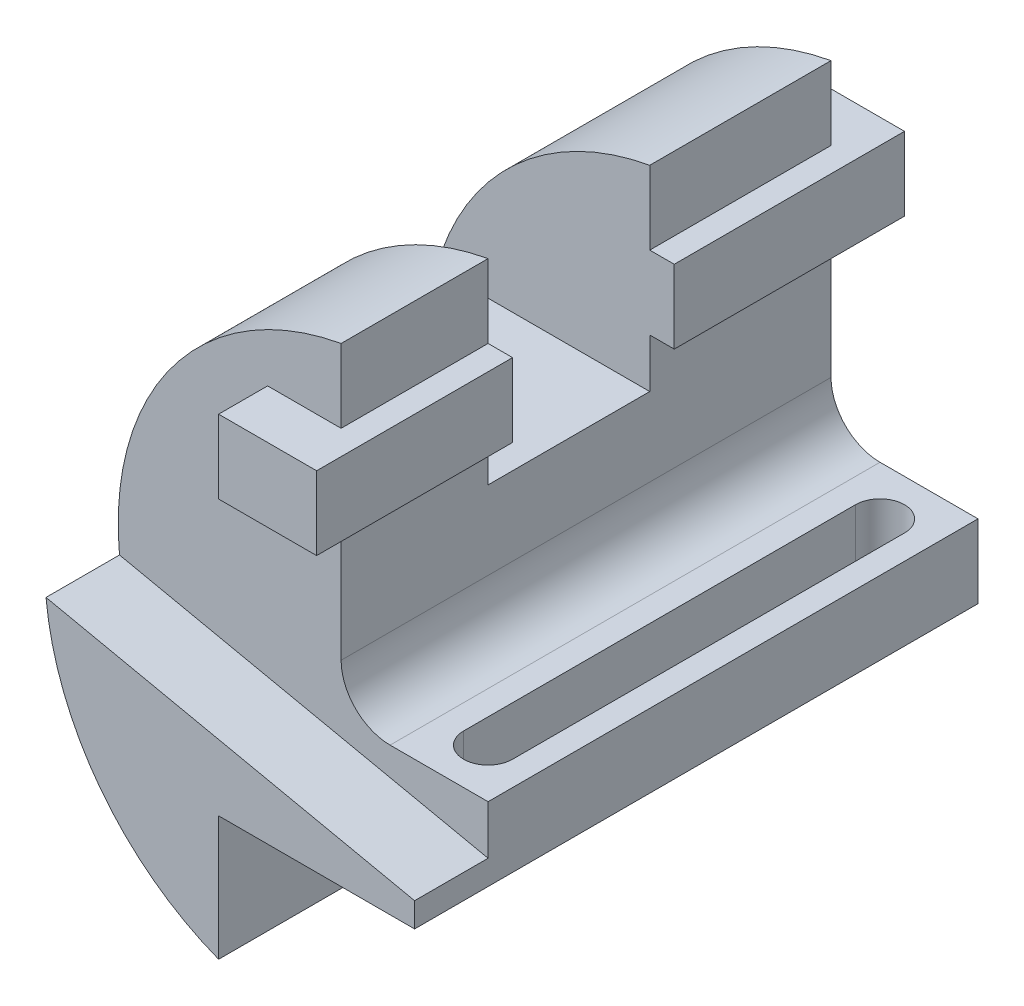
SolidWorks part; units mm, degrees
material "1060 Alloy"
ref_plane "Front Plane" through (0, 0, 0) normal (0, 0, 1) x (1, 0, 0)
ref_plane "Top Plane" through (0, 0, 0) normal (0, 1, 0) x (1, 0, 0)
ref_plane "Right Plane" through (0, 0, 0) normal (1, 0, 0) x (0, 0, -1)
sketch "Sketch1" plane through (0, 0, 0) normal (0, 0, 1) x (1, 0, 0)
  line L0 (0, 0) -> (-40, 0)
  line L1 (-40, 0) -> (-40, -25.3628)
  line L2 (0, 0) -> (0, 15)
  line L3 (0, 15) -> (-30, 15)
  line L4 (-30, 15) -> (-30, 81)
  arc A0 (-40, -25.3628) -> (-30, 81) centre (-20, 26.4083) cw
  dimension "D5" = 55.5
  dimension "D1" = 40
  dimension "D2" = 15
  dimension "D3" = 30
  dimension "D4" = 10
  dimension "D6" = 66
extrude "Boss-Extrude1" add sketch "Sketch1" along normal blind 115
sketch "Sketch2" plane through (0, 0, 115) normal (0, 0, 1) x (1, 0, 0)
  line L0 (0, 5) -> (-75.235, 20.9917)
  line L1 (0, 0) -> (0, 15) construction
  line L7 (0, 0) -> (0, 15)
  line L8 (0, 15) -> (-30, 15)
  line L9 (-30, 15) -> (-30, 81)
  line L10 (-40, -25.3628) -> (-40, 0)
  line L11 (-40, 0) -> (0, 0)
  line L12 (0, 5) -> (0, 15)
  line L13 (0, 15) -> (-30, 15)
  line L14 (-30, 15) -> (-30, 81)
  arc A1 (-30, 81) -> (-40, -25.3628) centre (-20, 26.4083) ccw
  arc A2 (-30, 81) -> (-75.235, 20.9917) centre (-20, 26.4083) ccw
  dimension "D1" = 78
  dimension "D2" = 5
  dimension "D3" = 0
extrude "Cut-Extrude1" cut sketch "Sketch2" against normal blind 15
sketch "Sketch3" plane through (0, 0, 0) normal (0, 0, -1) x (-1, 0, 0)
  line L0 (30, 15) -> (30, 81) construction
  line L1 (25, 66) -> (45, 66)
  line L2 (25, 66) -> (25, 51)
  line L3 (25, 51) -> (45, 51)
  line L4 (45, 66) -> (45, 51)
  dimension "D1" = 5
  dimension "D2" = 20
  dimension "D3" = 15
  dimension "D4" = 15
extrude "Boss-Extrude2" add sketch "Sketch3" against normal offset from surface 5 and the other way blind 10 up to face at (-32.3604, -0.8725, 115)
sketch "Sketch4" plane through (-30, 0, 0) normal (1, 0, 0) x (0, 0, -1)
  line L0 (-100, 81) -> (0, 81) construction
  line L1 (-70, 81) -> (-37, 81)
  line L2 (-70, 81) -> (-70, 41)
  line L3 (-70, 41) -> (-37, 41)
  line L4 (-37, 81) -> (-37, 41)
  line L5 (-100, 66) -> (-100, 81) construction
  line L6 (10, 51) -> (-110, 51) construction
  dimension "D1" = 33
  dimension "D2" = 30
  dimension "D3" = 10
extrude "Cut-Extrude3" cut sketch "Sketch4" against normal through all both and the other way through all
sketch "Sketch5" plane through (0, 15, 0) normal (0, 1, 0) x (1, 0, 0)
  line L0 (-10, -10) -> (-10, -90) construction
  line L1 (-5, -10) -> (-5, -90)
  line L2 (-15, -10) -> (-15, -90)
  line L3 (0, -100) -> (0, 0) construction
  line L4 (-75.235, -100) -> (0, -100) construction
  arc A0 (-5, -10) -> (-15, -10) centre (-10, -10) ccw
  arc A1 (-15, -90) -> (-5, -90) centre (-10, -90) ccw
  point P2 (-10, -50)
  dimension "D1" = 80
  dimension "D2" = 10
  dimension "D3" = 10
  dimension "D4" = 10
extrude "Cut-Extrude4" cut sketch "Sketch5" against normal through all both and the other way through all
fillet "Fillet1" radius 10 1 edges at (-30, 15, 50)
equation "\"A\"= 55.5mm"
equation "\"B\"= 66mm"
equation "\"C\"= 33mm"
equation "\"D6@Sketch1\"=\"B\""
